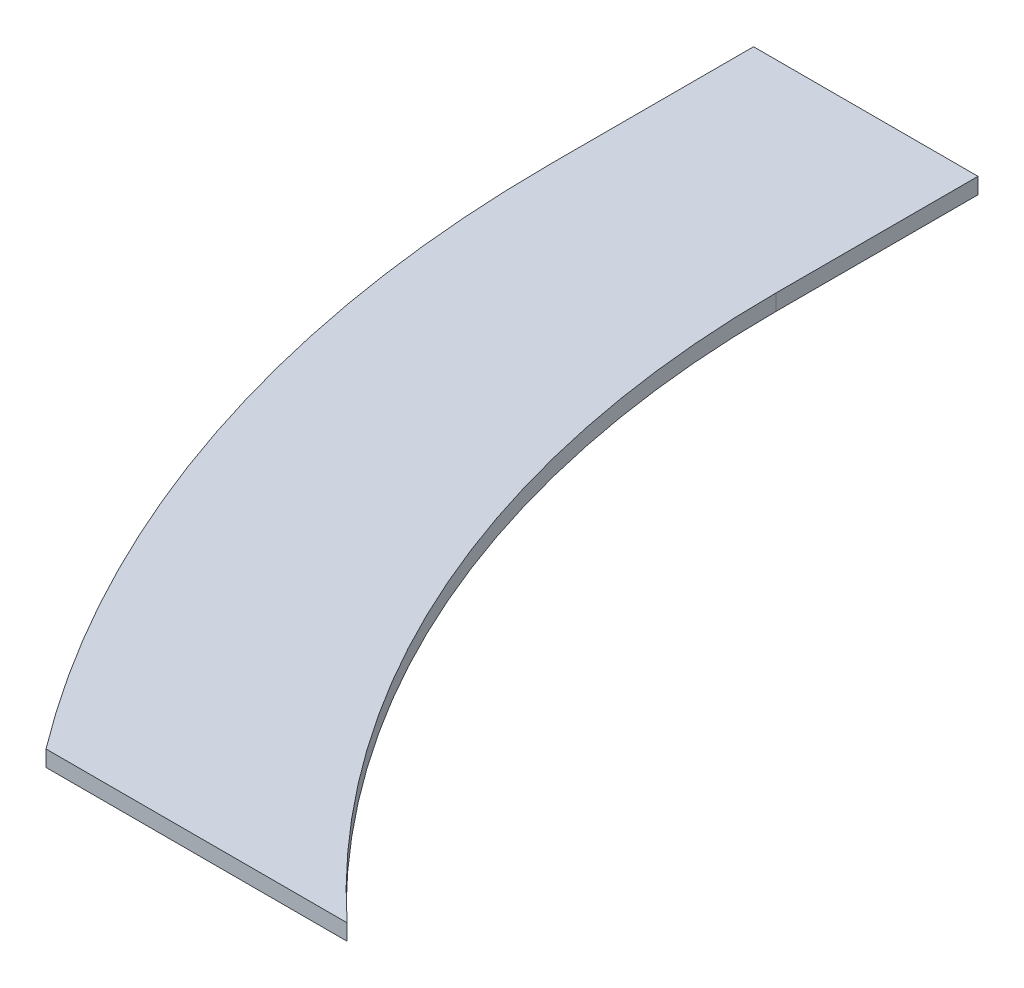
SolidWorks part; units mm, degrees
material "Pine"
ref_plane "Front Plane" through (0, 0, 0) normal (0, 0, 1) x (1, 0, 0)
ref_plane "Top Plane" through (0, 0, 0) normal (0, 1, 0) x (1, 0, 0)
ref_plane "Right Plane" through (0, 0, 0) normal (1, 0, 0) x (0, 0, -1)
sketch "Sketch2" plane through (0, 0, 0) normal (0, 1, 0) x (1, 0, 0)
  line L0 (0, 0) -> (-500, 0)
  line L1 (0, 0) -> (0, -500)
  circle A0 centre (0, 0) radius 500
  circle A1 centre (0, 0) radius 411.1
  dimension "D1" = 1000
  dimension "D2" = 88.9
extrude "Boss-Extrude1" add sketch "Sketch2" along normal blind 6.35 contours A1 L0 A0 L1
sketch "Sketch3" plane through (0, 0, 0) normal (0, 0, -1) x (-1, 0, 0)
  line L8 (411.1, 0) -> (500, 0)
  line L9 (500, 0) -> (500, 6.35)
  line L10 (500, 6.35) -> (411.1, 6.35)
  line L11 (411.1, 6.35) -> (411.1, 0)
  line L12 (411.1, 0) -> (500, 0)
  line L13 (500, 0) -> (500, 6.35)
  line L14 (500, 6.35) -> (411.1, 6.35)
  line L15 (411.1, 6.35) -> (411.1, 0)
  dimension "D1" = 0
extrude "Boss-Extrude2" add sketch "Sketch3" along normal blind 80
sketch "Sketch4" plane through (0, 6.35, 0) normal (0, 1, 0) x (1, 0, 0)
  line L1 (-500, 80) -> (0, 80) construction
  line L2 (-500, 80) -> (-500, -500) construction
  line L3 (-500, -500) -> (0, -500) construction
  line L4 (0, 80) -> (0, -500) construction
  line L5 (-500, 80) -> (-195.2, 80) construction
  line L6 (-500, 80) -> (-500, -326.4) construction
  line L7 (-500, -326.4) -> (-195.2, -326.4) construction
  line L8 (-195.2, 80) -> (-195.2, -326.4) construction
  line L9 (0, -500) -> (-406.4, -500) construction
  line L10 (0, -500) -> (0, -195.2) construction
  line L11 (0, -195.2) -> (-406.4, -195.2) construction
  line L12 (-406.4, -500) -> (-406.4, -195.2) construction
  dimension "D1" = 304.8
  dimension "D2" = 406.4
  dimension "D3" = 304.8
  dimension "D4" = 406.4
ref_plane "Plane1" through (0, 0, 301) normal (0, 0, -1) x (-1, 0, 0)
split "Split1" trim tools "Plane1" bodies to split 102 resulting bodies 104
